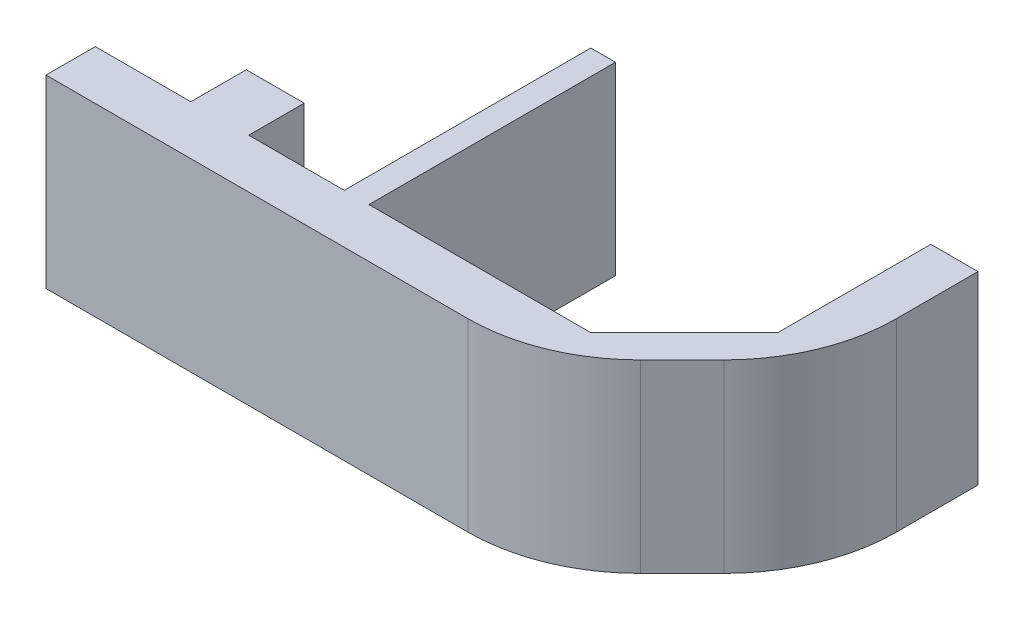
SolidWorks part; units mm, degrees
ref_plane "前基準面" through (0, 0, 0) normal (0, 0, 1) x (1, 0, 0)
ref_plane "上基準面" through (0, 0, 0) normal (0, 1, 0) x (1, 0, 0)
ref_plane "右基準面" through (0, 0, 0) normal (1, 0, 0) x (0, 0, -1)
sketch "草圖1" plane through (0, 0, 0) normal (0, 1, 0) x (1, 0, 0)
  line L0 (-27.5017, 6.8593) -> (-22.8017, 6.8593)
  line L1 (-22.8017, 6.8593) -> (-22.8017, 2.3593)
  line L2 (-22.8017, 2.3593) -> (4.9483, 2.3593)
  line L3 (4.9483, 2.3593) -> (12.5316, 9.9426)
  line L4 (12.5316, 9.9426) -> (12.5316, 22.3593)
  line L5 (-27.5017, 6.8593) -> (-27.5017, 2.3593)
  line L6 (-27.5017, 2.3593) -> (-35.2517, 2.3593)
  line L7 (-35.2517, 2.3593) -> (-35.2517, -1.6407)
  line L8 (-35.2517, -1.6407) -> (4.7783, -1.6407)
  line L12 (4.7783, -1.6407) -> (16.3616, 9.9426)
  line L13 (12.5316, 22.3593) -> (16.3616, 22.3593)
  line L14 (16.3616, 22.3593) -> (16.3616, 9.9426)
  dimension "D1" = 4.7
  dimension "D2" = 4.5
  dimension "D3" = 4
  dimension "D4" = 4
  dimension "D5" = 7.75
  dimension "D6" = 27.75
  dimension "D7" = 20
extrude "填料-伸長1" add sketch "草圖1" along normal blind 15
fillet "圓角1" radius 14 2 edges at (4.7783, 7.5, 1.6407) (16.3616, 7.5, -9.9426)
sketch "草圖2" plane through (0, 0, -2.3593) normal (0, 0, -1) x (-1, 0, 0)
  line L0 (-4.9483, 15) -> (22.8017, 15) construction
  line L1 (13.0517, 15) -> (15.0517, 15)
  line L2 (13.0517, 15) -> (13.0517, 0)
  line L3 (13.0517, 0) -> (15.0517, 0)
  line L4 (15.0517, 15) -> (15.0517, 0)
  line L5 (-4.9483, 0) -> (22.8017, 0) construction
  line L6 (35.2517, 15) -> (35.2517, 0) construction
  line L7 (22.8017, 15) -> (22.8017, 0) construction
  dimension "D1" = 20.2
  dimension "D2" = 2
extrude "填料-伸長2" add sketch "草圖2" along normal blind 20
